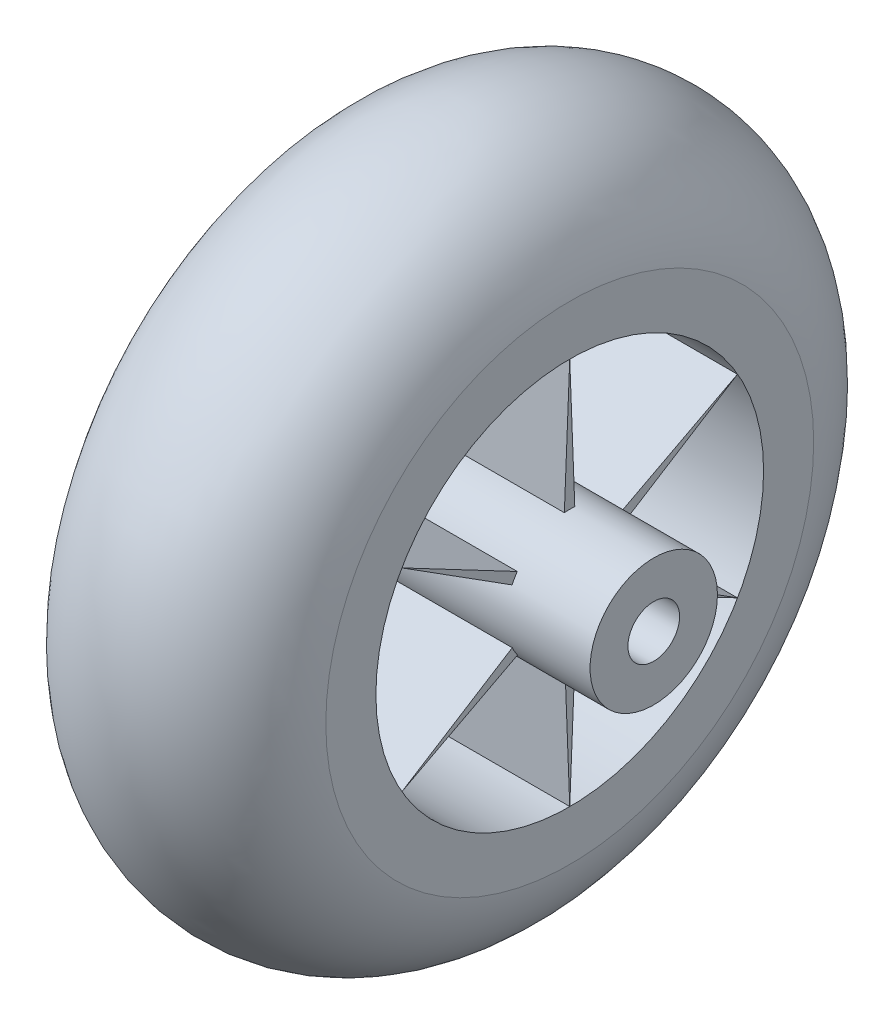
SolidWorks part; units mm, degrees
ref_plane "Front Plane" through (0, 0, 0) normal (0, 0, 1) x (1, 0, 0)
ref_plane "Top Plane" through (0, 0, 0) normal (0, 1, 0) x (1, 0, 0)
ref_plane "Right Plane" through (0, 0, 0) normal (1, 0, 0) x (0, 0, -1)
sketch "Sketch1" plane through (0, 0, 0) normal (0, 0, 1) x (1, 0, 0)
  line L0 (0, 0) -> (26.6, 0)
  line L1 (0, 0) -> (0, 5.4255)
  line L2 (26.6, 0) -> (26.6, 5.4255)
  line L3 (-4.7399, -21) -> (31.3399, -21) construction
  arc A1 (0, 5.4255) -> (26.6, 5.4255) centre (13.3, 3.3686) cw
  point P8 (13.3, 0)
  dimension "D1" = 21
revolve "Revolve10" add sketch "Sketch1" angle 360 about L3
sketch "Sketch13" plane through (26.6, 0, 0) normal (1, 0, 0) x (0, 0, -1)
  circle A0 centre (0, -21) radius 6.9
  dimension "D1" = 13.8
extrude "Boss-Extrude1" add sketch "Sketch13" along normal blind 9.1 and the other way blind 26.6 separate body
sketch "Sketch14" plane through (35.7, 0, 0) normal (1, 0, 0) x (0, 0, -1)
  circle A0 centre (0, -21) radius 2.8
  dimension "D1" = 5.6
extrude "Cut-Extrude1" cut sketch "Sketch14" against normal blind 9.1
sketch "Sketch16" plane through (26.6, 0, 0) normal (1, 0, 0) x (0, 0, -1)
  line L0 (0, 0) -> (-0.586, -14.1581)
  line L1 (0, 0) -> (0.5475, -14.1581)
  arc A0 (-0.586, -14.1581) -> (0.5475, -14.1581) centre (-0.0192, -20.7387) cw
extrude "Boss-Extrude2" add sketch "Sketch16" against normal blind 26.6
pattern_circular "CirPattern1" count 6 over 360 about axis through (0, -21, 0) along (1, 0, 0) of "Boss-Extrude2"
